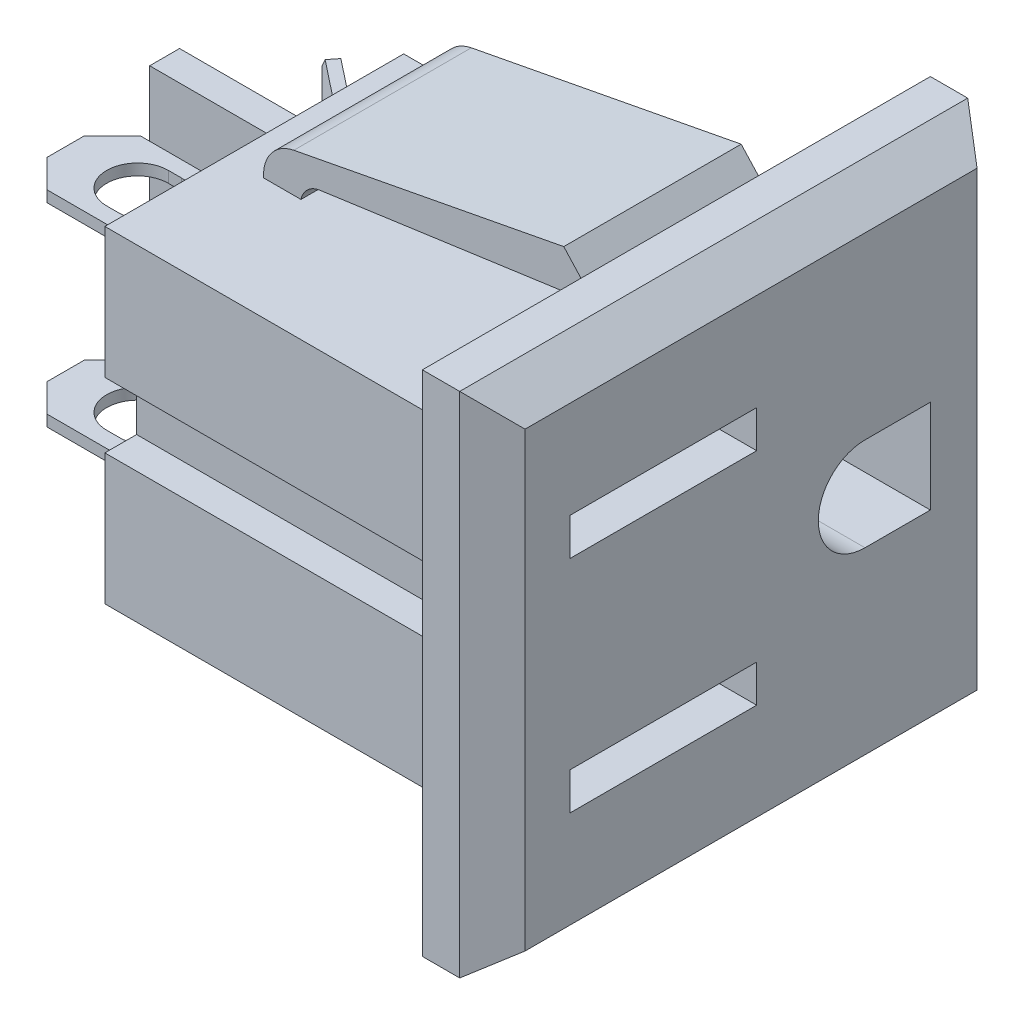
SolidWorks part; units mm, degrees
ref_plane "Alzado" through (0, 0, 0) normal (1, 0, 0) x (0, 1, 0)
ref_plane "Planta" through (0, 0, 0) normal (0, 0, 1) x (0, 1, 0)
ref_plane "Vista lateral" through (0, 0, 0) normal (0, 1, 0) x (-1, 0, 0)
sketch "Croquis1" plane through (0, 0, 0) normal (1, 0, 0) x (0, 1, 0)
  line L1 (-13.6, 13.6) -> (13.6, 13.6)
  line L2 (-13.6, 13.6) -> (-13.6, -13.6)
  line L3 (-13.6, -13.6) -> (13.6, -13.6)
  line L4 (13.6, 13.6) -> (13.6, -13.6)
  line L5 (-13.6, 13.6) -> (13.6, -13.6) construction
  line L6 (-13.6, -13.6) -> (13.6, 13.6) construction
  point P0 (0, 0)
  dimension "D1" = 27.2
extrude "Saliente-Extruir1" add sketch "Croquis1" against normal blind 4
chamfer "Chaflán1" distance 2 distance2 1.5 4 edges at (0, 0, 13.6) (0, 0, -13.6) (0, -13.6, 0) (0, 13.6, 0)
sketch "Croquis3" plane through (-4, 0, 0) normal (-1, 0, 0) x (0, -1, 0)
  line L0 (1.75, 10.6) -> (8.75, 10.6)
  line L1 (-8.75, 10.6) -> (-1.75, 10.6)
  line L2 (-8.75, 10.6) -> (-8.75, -5.4)
  line L3 (-8.75, -5.4) -> (-4.5, -5.4)
  line L4 (8.75, 10.6) -> (8.75, -5.4)
  line L6 (-1.75, 10.6) -> (-1.75, 8.9)
  line L7 (-1.75, 8.9) -> (1.75, 8.9)
  line L8 (1.75, 10.6) -> (1.75, 8.9)
  line L9 (4.5, -5.4) -> (8.75, -5.4)
  line L11 (-4.5, -5.4) -> (-4.5, -11.4)
  line L12 (-4.5, -11.4) -> (4.5, -11.4)
  line L13 (4.5, -5.4) -> (4.5, -11.4)
  line L14 (-13.6, 13.6) -> (13.6, 13.6) construction
  point P4 (8.75, -5.7491)
  point P10 (0, 8.9)
  point P15 (0, -11.4)
  point P16 (-8.75, -5.1379)
  dimension "D1" = 17.5
  dimension "D2" = 7
  dimension "D3" = 1.7
  dimension "D4" = 16
  dimension "D5" = 9
  dimension "D6" = 6
  dimension "D7" = 3
extrude "Saliente-Extruir2" add sketch "Croquis3" along normal blind 20
sketch "Croquis4" plane through (-4, 0, 0) normal (-1, 0, 0) x (0, -1, 0)
  line L12 (-12.1, -5.4) -> (-4.5, -5.4)
  line L13 (12.1, 13.6) -> (12.1, -12.1)
  line L14 (-12.1, -12.1) -> (-12.1, 13.6)
  line L15 (12.1, -12.1) -> (-12.1, -12.1)
  line L16 (12.1, -5.4) -> (12.1, -12.1)
  line L17 (-12.1, -12.1) -> (-12.1, -5.4)
  line L18 (12.1, -12.1) -> (-12.1, -12.1)
  line L19 (12.1, -5.4) -> (4.5, -5.4)
  line L30 (-8.75, 10.6) -> (-8.75, -5.4)
  line L31 (-8.75, -5.4) -> (-4.5, -5.4)
  line L32 (-4.5, -5.4) -> (-4.5, -11.4)
  line L33 (-4.5, -11.4) -> (4.5, -11.4)
  line L34 (4.5, -11.4) -> (4.5, -5.4)
  line L35 (4.5, -5.4) -> (8.75, -5.4)
  line L36 (8.75, -5.4) -> (8.75, 10.6)
  line L37 (8.75, 10.6) -> (1.75, 10.6)
  line L38 (1.75, 10.6) -> (1.75, 8.9)
  line L39 (1.75, 8.9) -> (-1.75, 8.9)
  line L40 (-1.75, 8.9) -> (-1.75, 10.6)
  line L41 (-1.75, 10.6) -> (-8.75, 10.6)
  line L44 (-4.5, -5.4) -> (-4.5, -11.4)
  line L45 (-4.5, -11.4) -> (4.5, -11.4)
  line L46 (4.5, -11.4) -> (4.5, -5.4)
  dimension "D1" = 1.5
  dimension "D2" = 0
extrude "Cortar-Extruir1" cut sketch "Croquis4" against normal blind 1.5
sketch "Croquis5" plane through (0, 0, -5.4) normal (0, 0, -1) x (1, 0, 0)
  line L0 (-18.9945, 9.6831) -> (-4.2395, 11.7568)
  line L1 (-4.2395, 11.7568) -> (-5.9284, 13.6)
  line L2 (-5.9284, 13.6) -> (-20.3789, 10.8434)
  line L3 (-24, 8.75) -> (-4, 8.75) construction
  line L4 (-4, 13.6) -> (-4, -13.6) construction
  line L5 (-24, 4.5) -> (-24, 8.75) construction
  line L6 (0, 0) -> (-24, 0) construction
  line L7 (0, 12.1) -> (0, -12.1) construction
  line L8 (-24, -4.5) -> (-24, 4.5) construction
  line L9 (-5.9284, -13.6) -> (-20.3789, -10.8434)
  line L10 (-4.2395, -11.7568) -> (-5.9284, -13.6)
  line L11 (-18.9945, -9.6831) -> (-4.2395, -11.7568)
  line L12 (-20, -8.75) -> (-22, -8.75)
  line L13 (-20, 8.75) -> (-22, 8.75)
  arc A0 (-18.9945, 9.6831) -> (-20, 8.75) centre (-18.8274, 8.4948) ccw
  arc A1 (-20.3789, 10.8434) -> (-22, 8.75) centre (-20.0042, 8.8788) ccw
  arc A2 (-20.3789, -10.8434) -> (-22, -8.75) centre (-20.0042, -8.8788) cw
  arc A3 (-18.9945, -9.6831) -> (-20, -8.75) centre (-18.8274, -8.4948) cw
  point P17 (-4, 13.6)
  point P30 (-4, -13.6)
  dimension "D3" = 16
  dimension "D5" = 1.2
  dimension "D6" = 2
  dimension "D1" = 14.9
  dimension "D2" = 2.5
  dimension "D4" = 2
  dimension "D7" = 8
  dimension "D8" = 2.8
  dimension "D9" = 55.5
extrude "Saliente-Extruir3" add sketch "Croquis5" against normal blind 9.5
sketch "Croquis6" plane through (-24, 0, 0) normal (-1, 0, 0) x (0, -1, 0)
  line L0 (-8.75, -5.4) -> (-4.5, -5.4) construction
  line L1 (-6.5, -0.3) -> (6.5, -0.3)
  line L2 (-6.5, -0.3) -> (-6.5, -1.9)
  line L3 (-6.5, -1.9) -> (6.5, -1.9)
  line L4 (6.5, -0.3) -> (6.5, -1.9)
  point P4 (0, -0.3)
  dimension "D1" = 1.6
  dimension "D2" = 13
  dimension "D3" = 3.5
extrude "Saliente-Extruir4" add sketch "Croquis6" along normal blind 8.5
sketch "Croquis7" plane through (-24, 0, 0) normal (-1, 0, 0) x (0, -1, 0)
  line L0 (0, 0) -> (0, 8.9) construction
  line L1 (-5.5, 9.7) -> (-4.9, 9.7)
  line L2 (-5.5, 9.7) -> (-5.5, -0.3)
  line L3 (-5.5, -0.3) -> (-4.9, -0.3)
  line L4 (-4.9, 9.7) -> (-4.9, -0.3)
  line L5 (1.75, 8.9) -> (-1.75, 8.9) construction
  line L6 (4.9, 9.7) -> (4.9, -0.3)
  line L7 (5.5, -0.3) -> (4.9, -0.3)
  line L8 (5.5, 9.7) -> (5.5, -0.3)
  line L9 (5.5, 9.7) -> (4.9, 9.7)
  line L10 (6.5, -0.3) -> (-6.5, -0.3) construction
  dimension "D1" = 0.6
  dimension "D2" = 10
  dimension "D3" = 9.8
extrude "Saliente-Extruir5" add sketch "Croquis7" along normal blind 8 separate body
sketch "Croquis8" plane through (0, 5.5, 0) normal (0, 1, 0) x (-1, 0, 0)
  line L0 (24, 4.7) -> (32, 4.7) construction
  line L1 (24, 9.7) -> (24, -0.3) construction
  line L2 (32, 9.7) -> (32, -0.3) construction
  line L3 (24, -0.3) -> (25, 0.7)
  line L4 (25, 0.7) -> (25, 2.2)
  line L5 (25, 2.2) -> (30.5, 2.2)
  line L6 (30.5, 2.2) -> (32, 3.7)
  line L7 (32, 5.7) -> (32, 9.7)
  line L8 (24, 10.6) -> (24, -5.4) construction
  line L9 (30.5, 7.2) -> (32, 5.7)
  line L10 (25, 7.2) -> (30.5, 7.2)
  line L11 (25, 8.7) -> (25, 7.2)
  line L12 (24, 9.7) -> (25, 8.7)
  line L13 (32, -0.3) -> (24, -0.3) construction
  line L14 (32, 9.7) -> (24, 9.7) construction
  line L15 (32, -0.3) -> (24, -0.3)
  line L16 (32, 9.7) -> (24, 9.7)
  line L17 (32, 3.7) -> (32, -0.3)
  line L18 (27.45, 4.7) -> (28.15, 4.7) construction
  line L19 (27.45, 6.35) -> (28.15, 6.35)
  line L20 (27.45, 3.05) -> (28.15, 3.05)
  arc A0 (27.45, 6.35) -> (27.45, 3.05) centre (27.45, 4.7) ccw
  arc A1 (28.15, 3.05) -> (28.15, 6.35) centre (28.15, 4.7) ccw
  point P23 (27.8, 4.7)
  point P28 (25.8, 4.7)
  point P29 (29.8, 4.7)
  point P30 (29.1526, 4.7)
  dimension "D1" = 1
  dimension "D2" = 45
  dimension "D3" = 2.5
  dimension "D4" = 45
  dimension "D5" = 5.5
  dimension "D6" = 4
  dimension "D7" = 3.3
  dimension "D8" = 2.2
  dimension "D9" = 10
extrude "Cortar-Extruir2" cut sketch "Croquis8" against normal through all
sketch "Croquis9" plane through (0, 0, 0) normal (0, 1, 0) x (-1, 0, 0)
  line L0 (24, -2.9) -> (32.8717, -9.9)
  line L1 (24, -2.9) -> (23.6283, -3.371)
  line L2 (32.8717, -9.9) -> (32.5, -10.371)
  line L3 (23.6283, -3.371) -> (32.5, -10.371)
  line L4 (24, 10.6) -> (24, -5.4) construction
  line L5 (24, -5.4) -> (24, -11.4) construction
  line L6 (32.5, -1.9) -> (24, -1.9) construction
  dimension "D1" = 0.6
  dimension "D2" = 8.5
  dimension "D3" = 8
  dimension "D4" = 1
extrude "Saliente-Extruir6" add sketch "Croquis9" along normal mid plane 10
sketch "Croquis10" plane through (-7.7984, 0, 9.8835) normal (-0.6194, 0, 0.7851) x (0.7851, 0, 0.6194)
  line L0 (-31.9383, 0) -> (-20.6376, 0) construction
  line L1 (-31.9383, 5) -> (-31.9383, -5) construction
  line L2 (-31.9383, -1.5) -> (-31.9383, -5)
  line L3 (-20.6376, 5) -> (-20.6376, -5) construction
  line L4 (-21.111, -5) -> (-21.111, -4)
  line L5 (-21.111, -5) -> (-21.111, 5) construction
  line L6 (-21.111, -4) -> (-25.9383, -3.1)
  line L7 (-30.9383, 2.5) -> (-31.9383, 1.5)
  line L8 (-25.9383, -3.1) -> (-25.9383, -2.5)
  line L9 (-25.9383, -2.5) -> (-30.9383, -2.5)
  line L10 (-31.9383, 1.5) -> (-31.9383, 5)
  line L11 (-30.9383, -2.5) -> (-31.9383, -1.5)
  line L12 (-25.9383, 2.5) -> (-30.9383, 2.5)
  line L13 (-25.9383, 3.1) -> (-25.9383, 2.5)
  line L14 (-21.111, 4) -> (-25.9383, 3.1)
  line L15 (-21.111, 5) -> (-21.111, 4)
  line L16 (-31.9383, -5) -> (-21.111, -5)
  line L17 (-31.9383, 5) -> (-21.111, 5)
  line L18 (-28.0883, 0) -> (-27.3883, 0) construction
  line L19 (-28.0883, 1.65) -> (-27.3883, 1.65)
  line L20 (-28.0883, -1.65) -> (-27.3883, -1.65)
  arc A0 (-28.0883, 1.65) -> (-28.0883, -1.65) centre (-28.0883, 0) ccw
  arc A1 (-27.3883, -1.65) -> (-27.3883, 1.65) centre (-27.3883, 0) ccw
  point P19 (-27.7383, 0)
  point P33 (-29.7383, 0)
  point P34 (-25.7383, 0)
  dimension "D1" = 1
  dimension "D2" = 45
  dimension "D3" = 1
  dimension "D4" = 5
  dimension "D5" = 0.6
  dimension "D6" = 5
  dimension "D7" = 2.2
  dimension "D8" = 4
  dimension "D9" = 3.3
extrude "Cortar-Extruir3" cut sketch "Croquis10" against normal up to next (0.6 mm away)
sketch "Croquis11" plane through (0, 0, 0) normal (1, 0, 0) x (0, 1, 0)
  line L0 (-6.5, -0.3) -> (6.5, -0.3) construction
  line L1 (-4.9, -0.3) -> (-6.9, -0.3)
  line L2 (-4.9, -0.3) -> (-4.9, 9.7)
  line L3 (-4.9, 9.7) -> (-6.9, 9.7)
  line L4 (-6.9, -0.3) -> (-6.9, 9.7)
  line L5 (4.9, 9.7) -> (6.9, 9.7)
  line L6 (4.9, 9.7) -> (4.9, -0.3)
  line L7 (4.9, -0.3) -> (6.9, -0.3)
  line L8 (6.9, 9.7) -> (6.9, -0.3)
  line L9 (-2.5, -9.6) -> (2.5, -9.6)
  line L10 (-2.5, -9.6) -> (-2.5, -6.1)
  line L11 (2.5, -9.6) -> (2.5, -6.1)
  line L12 (-12.1, -12.1) -> (12.1, -12.1) construction
  arc A0 (-2.5, -6.1) -> (2.5, -6.1) centre (0, -6.1) cw
  point P10 (0, -9.6)
  point P22 (0, -3.6)
  dimension "D1" = 2
  dimension "D2" = 5
  dimension "D3" = 3.5
  dimension "D4" = 2.5
  dimension "D5" = 2.5
extrude "Cortar-Extruir4" cut sketch "Croquis11" against normal blind 23.5
sketch "Croquis12" plane through (-23.5, 0, 0) normal (1, 0, 0) x (0, 1, 0)
  line L1 (-6.9, 9.7) -> (-5.5, 9.7)
  line L2 (-6.9, 9.7) -> (-6.9, -0.3)
  line L3 (-6.9, -0.3) -> (-5.5, -0.3)
  line L4 (-5.5, 9.7) -> (-5.5, -0.3)
  line L5 (5.5, 9.7) -> (6.9, 9.7)
  line L6 (5.5, 9.7) -> (5.5, -0.3)
  line L7 (5.5, -0.3) -> (6.9, -0.3)
  line L8 (6.9, 9.7) -> (6.9, -0.3)
  line L12 (-2.25, -5.0103) -> (2.25, -5.0103)
  arc A0 (2.5, -6.1) -> (-2.5, -6.1) centre (0, -6.1) ccw construction
  arc A1 (2.25, -5.0103) -> (-2.25, -5.0103) centre (0, -6.1) ccw
  point P12 (4, -3.6643)
  point P13 (0, 0)
  point P17 (-2.4552, -5.629)
  dimension "D1" = 4.5
extrude "Cortar-Extruir5" cut sketch "Croquis12" against normal blind 0.55
